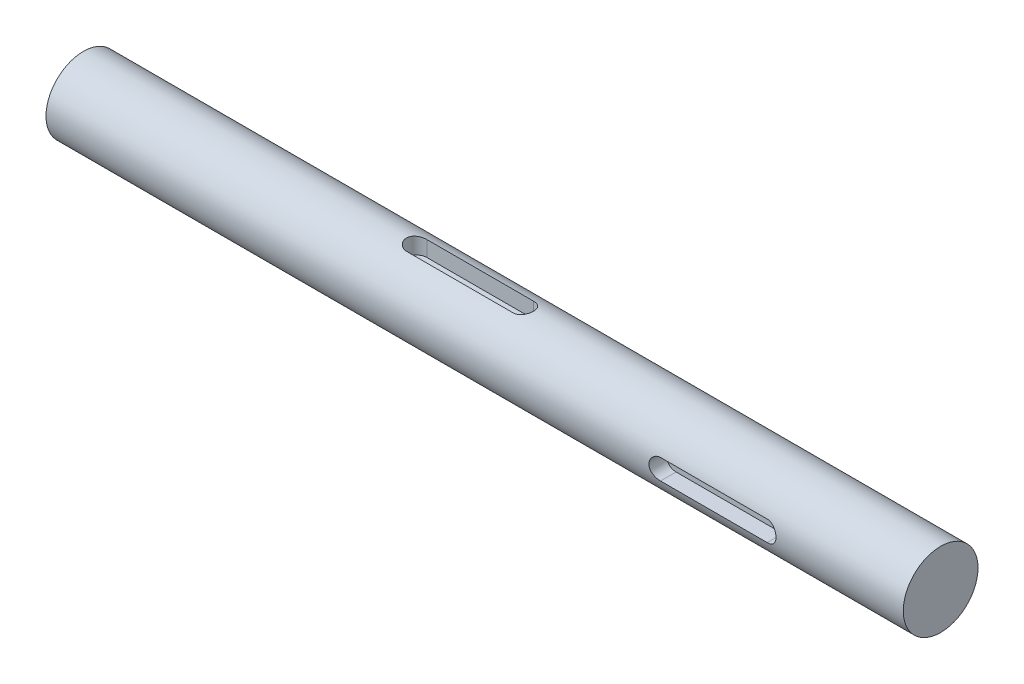
SolidWorks part; units mm, degrees
ref_plane "Front Plane" through (0, 0, 0) normal (0, 0, 1) x (1, 0, 0)
ref_plane "Top Plane" through (0, 0, 0) normal (0, 1, 0) x (1, 0, 0)
ref_plane "Right Plane" through (0, 0, 0) normal (1, 0, 0) x (0, 0, -1)
sketch "Sketch1" plane through (0, 0, 0) normal (0, 0, 1) x (1, 0, 0)
  line L0 (0, 0) -> (140, 0) construction
  line L1 (140, 0) -> (140, 11)
  line L2 (140, 11) -> (0, 11)
  line L3 (0, 11) -> (0, 0)
  line L4 (0, 0) -> (140, 0)
  dimension "D1" = 22
  dimension "D2" = 140
revolve "Revolve1" add sketch "Sketch1" angle 360 about L0
sketch "Sketch3" plane through (140, 0, 0) normal (1, 0, 0) x (0, 0, -1)
  line L0 (11, 0) -> (-11, 0) construction
  line L1 (0, 11) -> (0, -11) construction
  circle A0 centre (0, 0) radius 11 construction
ref_plane "Plane1" through (0, 11, 0) normal (0, 1, 0) x (1, 0, 0)
sketch "Sketch4" plane through (0, 11, 0) normal (0, 1, 0) x (1, 0, 0)
  line L0 (129.52, 0) -> (98.12, 0) construction
  line L1 (129.52, -3) -> (98.12, -3)
  line L2 (129.52, 3) -> (98.12, 3)
  line L4 (132.52, 0) -> (140, 0) construction
  line L5 (140, -11) -> (140, 11) construction
  arc A0 (129.52, -3) -> (129.52, 3) centre (129.52, 0) ccw
  arc A1 (98.12, 3) -> (98.12, -3) centre (98.12, 0) ccw
  point P3 (113.82, 0)
  point P13 (95.12, 0)
  dimension "D1" = 7.48
  dimension "D2" = 37.4
  dimension "D3" = 6
extrude "Cut-Extrude1" cut sketch "Sketch4" against normal blind 5
ref_plane "Plane2" through (0, 0, 0) normal (0, 1, 0) x (0, 0, 1)
mirror "Mirror1" about plane through (0, 0, 0) normal (0, 1, 0) of "Cut-Extrude1"
sketch "Sketch5" plane through (140, 0, 0) normal (1, 0, 0) x (0, 0, -1)
  circle A0 centre (0, 0) radius 11
extrude "Boss-Extrude1" add sketch "Sketch5" along normal blind 97.36
sketch "Sketch6" plane through (237.36, 0, 0) normal (1, 0, 0) x (0, 0, -1)
  line L0 (0, 11) -> (0, -11) construction
  line L2 (11, 0) -> (-11, 0) construction
  circle A0 centre (0, 0) radius 11 construction
ref_plane "Plane3" through (0, 0, 11) normal (0, 0, 1) x (1, 0, 0)
sketch "Sketch7" plane through (0, 0, 11) normal (0, 0, 1) x (1, 0, 0)
  line L0 (211.88, 0) -> (180.48, 0) construction
  line L1 (211.88, -3) -> (180.48, -3)
  line L2 (211.88, 3) -> (180.48, 3)
  line L3 (177.48, 11) -> (177.48, -11) construction
  line L4 (12.1, 11) -> (-12.1, 11) construction
  line L5 (132.5199, -11) -> (237.36, -11) construction
  line L6 (132.52, -11) -> (132.52, 11) construction
  line L7 (160, 11) -> (160, -11) construction
  arc A0 (211.88, -3) -> (211.88, 3) centre (211.88, 0) ccw
  arc A1 (180.48, 3) -> (180.48, -3) centre (180.48, 0) ccw
  point P3 (196.18, 0)
  point P19 (214.88, 0)
  dimension "D1" = 6
  dimension "D2" = 37.4
  dimension "D3" = 17.48
  dimension "D4" = 27.48
extrude "Cut-Extrude2" cut sketch "Sketch7" against normal blind 5
ref_plane "Plane4" through (0, 0, 0) normal (0, 0, 1) x (0, -1, 0)
mirror "Mirror2" about plane through (0, 0, 0) normal (0, 0, 1) of "Cut-Extrude2"
sketch "Sketch8" plane through (237.36, 0, 0) normal (1, 0, 0) x (0, 0, -1)
  circle A0 centre (0, 0) radius 11
extrude "Boss-Extrude2" add sketch "Sketch8" along normal blind 15
